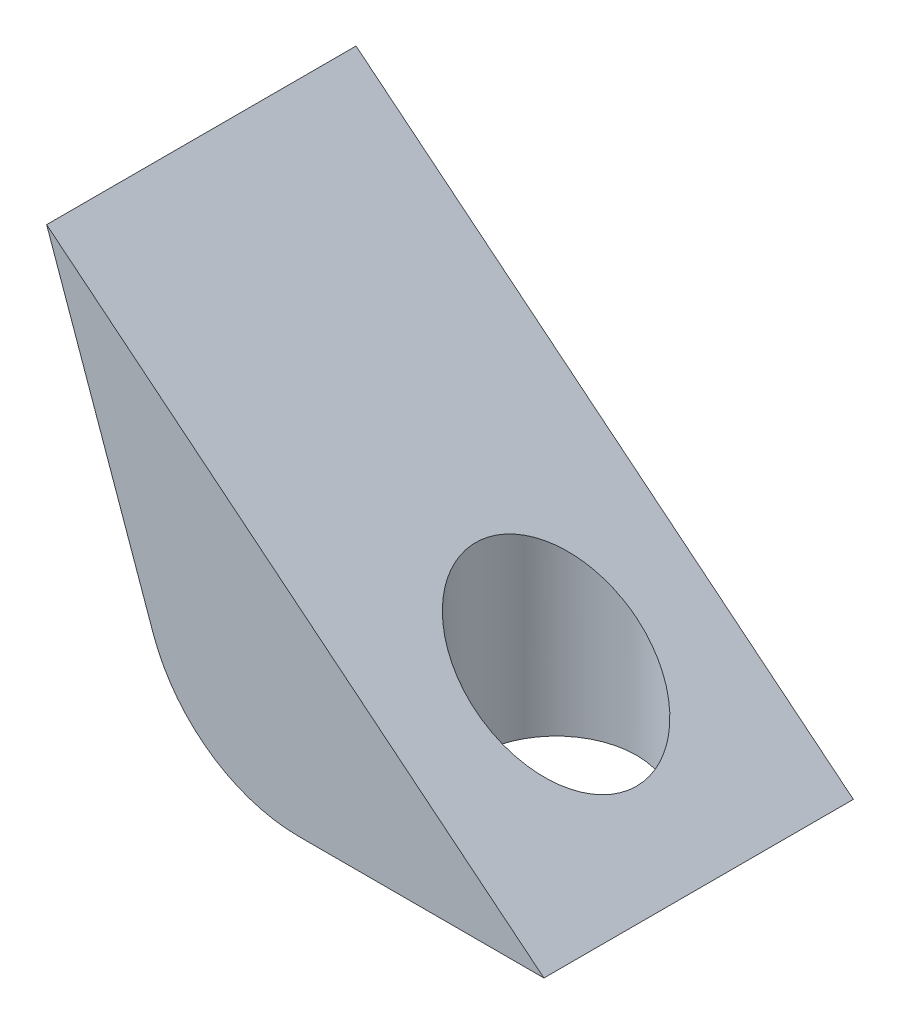
SolidWorks part; units mm, degrees
ref_plane "Front Plane" through (0, 0, 0) normal (0, 0, 1) x (1, 0, 0)
ref_plane "Top Plane" through (0, 0, 0) normal (0, 1, 0) x (1, 0, 0)
ref_plane "Right Plane" through (0, 0, 0) normal (1, 0, 0) x (0, 0, -1)
sketch "Sketch2" plane through (0, 0, 0) normal (0, 0, 1) x (1, 0, 0)
  line L0 (0, 0) -> (11.45, 0)
  line L1 (0, 0) -> (-4.6231, 13.05)
  line L2 (-4.6231, 13.05) -> (11.45, 0)
  dimension "D1" = 13.05
  dimension "D2" = 11.45
  dimension "D3" = 109.507
extrude "Boss-Extrude1" add sketch "Sketch2" along normal blind 10
fillet "Fillet1" radius 5 1 edges at (0, 0, 5)
sketch "Sketch3" plane through (0, 0, 10) normal (0, 0, 1) x (1, 0, 0)
  line L0 (-4.6231, 13.05) -> (-1.1798, 3.3304) construction
  dimension "D1" = 9.7196
sketch "Sketch4" plane through (0, 0, 0) normal (0, -1, 0) x (1, 0, 0)
  line L0 (6.7132, 4.87) -> (3.5332, 4.87) construction
  line L4 (3.5332, 10) -> (3.5332, 0) construction
  circle A0 centre (6.7132, 4.87) radius 2.6
  dimension "D2" = 5.2
  dimension "D1" = 3.18
  dimension "D3" = 5.13
extrude "Cut-Extrude1" cut sketch "Sketch4" against normal blind 10
